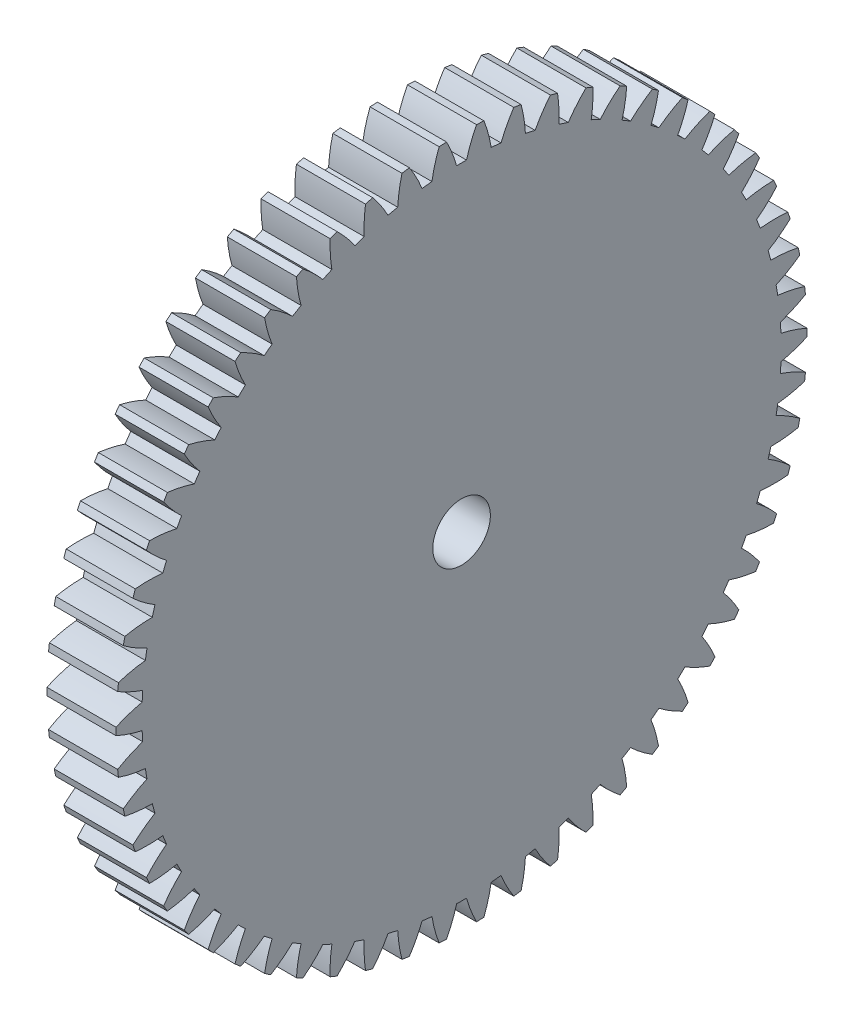
SolidWorks part; units mm, degrees
ref_plane "Plane1" through (0, 0, 0) normal (0, 0, 1) x (1, 0, 0)
ref_plane "Plane2" through (0, 0, 0) normal (0, 1, 0) x (1, 0, 0)
ref_plane "Plane3" through (0, 0, 0) normal (1, 0, 0) x (0, 0, -1)
other "Configuration Table"
sketch "HoldingSke" plane through (0, 0, 0) normal (0, 1, 0) x (1, 0, 0)
  line L0 (0, 0) -> (0.5299, -0.848)
  line L1 (-15, 0) -> (100, 0) construction
  line L2 (0, 0) -> (-2.1039, 2.3779)
  line L3 (0, 0) -> (-11.863, 4.5341)
  line L4 (0, 0) -> (4.5764, 7.3237)
  line L5 (0, 0) -> (-46.8476, -17.4728)
  line L6 (0, 0) -> (-4.9738, -3.3558)
  line L7 (-2.1039, 2.3779) -> (8.6586, 51.2059)
  line L8 (-76.2, 54.61) -> (-75.3, 54.61)
  line L9 (-71.009, 38.7566) -> (-53.1078, 45.2721)
  line L10 (-76.2, 71.12) -> (104.1128, 71.12)
  line L11 (0, 0) -> (-6, 0)
  line L12 (-76.2, 101.6) -> (-76.162, 101.6)
  line L13 (24.9733, 27.94) -> (52.9518, 28.4284)
  line L14 (24.9733, 27.94) -> (24.9743, 27.94)
  line L15 (24.9733, 27.94) -> (100.4006, 29.5858)
  line L16 (-63.627, -1) -> (-12.827, -1)
  circle A0 centre (0, 0) radius 2.5
  circle A1 centre (0, 0) radius 27.749
  circle A2 centre (0, 0) radius 37.5
  circle A3 centre (0, 0) radius 2.5
  dimension "MHD" = 55.498
  dimension "Hub_dia" = 75
  dimension "Bore" = 5
  dimension "MBD" = 5
  dimension "Num_teeth" = 58
  dimension "Pitch" = 1
  dimension "Overall_len" = 50
  dimension "Show_teeth" = 58
  dimension "Thickness" = 6
  dimension "OAL" = 50.0001
  dimension "T_dim" = 0.9
  dimension "Ap" = 20
  dimension "H" = 19.05
  dimension "Pitch_radius" = 180.3128
  dimension "Width" = 6
  dimension "Backlash" = 0.038
  dimension "Addendum_fac" = 1
  dimension "Dedendum_fac" = 1.25
  dimension "Clearance_fac" = 0.25
  dimension "Dedendum_add" = 0.001
  dimension "Module" = 1
sketch "BasProSke" plane through (0, 0, 0) normal (0, 1, 0) x (1, 0, 0)
  line L0 (-10, 0) -> (60, 0) construction
  line L1 (0, 0) -> (0, 30)
  line L2 (0, 0) -> (6, 0)
  line L3 (6, 0) -> (6, 30)
  line L4 (6, 30) -> (0, 30)
  dimension "Thickness" = 6
  dimension "Diameter" = 60
revolve "Base-Revolve" add sketch "BasProSke" angle 360 about L0
sketch "TooCutSke" plane through (0, 0, 0) normal (1, 0, 0) x (0, 0, -1)
  line L1 (0, 0) -> (0, 107) construction
  line L2 (0, 0) -> (-0.8518, 28.9875) construction
  line L3 (0, 0) -> (-3.1391, 57.8971) construction
  line L4 (-0.8518, 28.9875) -> (-1.5695, 28.9486) construction
  arc A0 (0.4315, 27.7456) -> (-0.4315, 27.7456) centre (0, 0) ccw
  arc A1 (1.3156, 29.9966) -> (-1.3156, 29.9966) centre (0, 0) ccw
  circle A2 centre (0, 0) radius 29 construction
  circle A3 centre (0, 0) radius 27.2511 construction
  arc A4 (-0.4315, 27.7456) -> (-1.3156, 29.9966) centre (-11.6117, 24.6534) ccw
  arc A5 (1.3156, 29.9966) -> (0.4315, 27.7456) centre (11.6117, 24.6534) ccw
  dimension "Root_dia" = 55.498
  dimension "Overcut_dia" = 60.0508
  dimension "Pitch_dia" = 58
  dimension "Base_dia" = 54.5022
  dimension "Flank_rad" = 11.6
  dimension "Half_ang" = 3.103
  dimension "Half_CT" = 0.7188
extrude "ToothCut" cut sketch "TooCutSke" along normal through all
fillet "Breaks" [suppressed] radius 0.02
fillet "RootFillets" [suppressed] radius 0.251
pattern_circular "TeethCuts" count 58 every 6.207 about axis through (-10, 0, 0) along (1, 0, 0) of "ToothCut", "RootFillets", "Breaks"
sketch "HubNeaOneSke" plane through (0, 0, 0) normal (-1, 0, 0) x (0, 0, 1)
  circle A0 centre (0, 0) radius 27.749
  dimension "Diameter" = 55.498
extrude "HubNearOne" [suppressed] add sketch "HubNeaOneSke" along normal blind 44.0001
sketch "HubNeaBotSke" plane through (0, 0, 0) normal (-1, 0, 0) x (0, 0, 1)
  circle A0 centre (0, 0) radius 27.749
  dimension "Diameter" = 55.498
extrude "HubNearBoth" [suppressed] add sketch "HubNeaBotSke" along normal blind 22
ref_plane "FarPln" through (6, 0, 0) normal (1, 0, 0) x (0, 0, -1)
sketch "HubFarSke" plane through (6, 0, 0) normal (1, 0, 0) x (0, 0, -1)
  circle A0 centre (0, 0) radius 27.749
  dimension "Diameter" = 55.498
extrude "HubFar" [suppressed] add sketch "HubFarSke" along normal blind 22
sketch "BorSke" plane through (0, 0, 0) normal (1, 0, 0) x (0, 0, -1)
  circle A0 centre (0, 0) radius 2.5
  dimension "Diameter" = 5
extrude "Bore" cut sketch "BorSke" along normal mid plane 100.0001
sketch "KeySke" plane through (0, 0, 0) normal (1, 0, 0) x (0, 0, -1)
  line L0 (-1, 0) -> (-1, 3.4)
  line L1 (-1, 3.4) -> (1, 3.4)
  line L2 (1, 3.4) -> (1, 0)
  line L3 (0, 0) -> (0, 34) construction
  line L4 (-1, 0) -> (1, 0)
  dimension "Offset" = 3.4
  dimension "Width" = 2
extrude "Keyway" [suppressed] cut sketch "KeySke" along normal mid plane 100.0001
pattern_circular "Keyway2" [suppressed] count 2 every 90 about axis through (-10, 0, 0) along (1, 0, 0)
equation "' \"Module@HoldingSke\" = 6.35"
equation "' \"Num_teeth@HoldingSke\" = 12"
equation "' \"Ap@HoldingSke\" =  20"
equation "' \"Ap@HoldingSke\" = 20"
equation "' \"Width@HoldingSke\" = 0.5 * 25.4"
equation "' \"Hub_dia@HoldingSke\"= 1 * 25.4"
equation "' \"Hub_dia@HoldingSke\" = 1 * 25.4"
equation "' \"Overall_len@HoldingSke\" = 1.0 * 25.4"
equation "' \"Bore@HoldingSke\" = 0.75 * 25.4"
equation "' \"T_dim@HoldingSke\" = 0.1 * 25.4"
equation "' \"Width@KeySke\" = 0.25 * 25.4"
equation "' \"Show_teeth@HoldingSke\" = 13"
equation "' \"Backlash@HoldingSke\" = 0.009 * 25.4"
equation "' \"Addendum_fac@HoldingSke\" = 1.0"
equation "' \"Dedendum_fac@HoldingSke\" = 1.25"
equation "' \"Dedendum_add@HoldingSke\" = 0.00005 * 25.4"
equation "' \"Clearance_fac@HoldingSke\" = 0.25"
equation "\"Pitch@HoldingSke\" = 1 / \"Module@HoldingSke\""
equation "\"Overcut_dia@TooCutSke\" = (\"Num_teeth@HoldingSke\" + 2 * \"Addendum_fac@HoldingSke\") / \"Pitch@HoldingSke\" + 0.002 * 25.4"
equation "\"Pitch_dia@TooCutSke\" = \"Num_teeth@HoldingSke\" / \"Pitch@HoldingSke\""
equation "\"Base_dia@TooCutSke\" = \"Num_teeth@HoldingSke\" / \"Pitch@HoldingSke\" * cos((\"Ap@HoldingSke\"  * 3.14159265 / 180))"
equation "\"Root_dia@TooCutSke\" = (\"Num_teeth@HoldingSke\" + 2) / \"Pitch@HoldingSke\" - 2 * (\"Addendum_fac@HoldingSke\" + \"Dedendum_fac@HoldingSke\") / \"Pitch@HoldingSke\" - \"Dedendum_add@HoldingSke\" * 2"
equation "\"Half_ang@TooCutSke\" = 180 / \"Num_teeth@HoldingSke\""
equation "\"Half_CT@TooCutSke\" = \"Num_teeth@HoldingSke\" / \"Pitch@HoldingSke\" * sin((3.14159265 / 2 / \"Num_teeth@HoldingSke\")) / 2 - 7 * \"Backlash@HoldingSke\" / 4"
equation "\"Flank_rad@TooCutSke\" = \"Num_teeth@HoldingSke\" / \"Pitch@HoldingSke\" / 5"
equation "\"Radius@RootFillets\" = \"Clearance_fac@HoldingSke\" / \"Pitch@HoldingSke\" + \"Dedendum_add@HoldingSke\""
equation "\"Break_rad@Breaks\" = 0.02 / \"Pitch@HoldingSke\""
equation "\"Thickness@HoldingSke\" = \"Width@HoldingSke\""
equation "\"OAL@HoldingSke\" = \"Thickness@HoldingSke\""
equation "\"MHD@HoldingSke\" = (\"Num_teeth@HoldingSke\" + 2) / \"Pitch@HoldingSke\" - 2 * (\"Addendum_fac@HoldingSke\" + \"Dedendum_fac@HoldingSke\")  / \"Pitch@HoldingSke\" - \"Dedendum_add@HoldingSke\" * 2"
equation "\"MBD@HoldingSke\" = (\"Num_teeth@HoldingSke\" + 2) / \"Pitch@HoldingSke\" - 2 * (\"Addendum_fac@HoldingSke\" + \"Dedendum_fac@HoldingSke\")  / \"Pitch@HoldingSke\" - \"Dedendum_add@HoldingSke\" * 2 - 0.002 * 25.4"
equation "\"MHD@HoldingSke\" = ((sgn( \"MHD@HoldingSke\" - \"Hub_dia@HoldingSke\" )-1)*( \"MHD@HoldingSke\" - \"Hub_dia@HoldingSke\" ))/-2+ \"Hub_dia@HoldingSke\""
equation "\"MBD@HoldingSke\" = ((sgn( \"MBD@HoldingSke\" - \"Bore@HoldingSke\" )-1)*( \"MBD@HoldingSke\" - \"Bore@HoldingSke\" ))/-2+ \"Bore@HoldingSke\""
equation "\"OAL@HoldingSke\" = ((sgn( \"OAL@HoldingSke\" - \"Overall_len@HoldingSke\" )+1)*( \"OAL@HoldingSke\" - \"Overall_len@HoldingSke\" ))/2 + \"Overall_len@HoldingSke\" + 0.000002 * 25.4"
equation "\"Num_teeth@TeethCuts\" = int( \"Show_teeth@HoldingSke\" ) + 1"
equation "\"Num_teeth@TeethCuts\" = ((sgn( \"Num_teeth@TeethCuts\" - \"Num_teeth@HoldingSke\" )-1)*( \"Num_teeth@TeethCuts\" - \"Num_teeth@HoldingSke\" ))/-2+ \"Num_teeth@HoldingSke\""
equation "\"Num_teeth@TeethCuts\" = ((sgn( \"Num_teeth@TeethCuts\" - 2.0)+1)*( \"Num_teeth@TeethCuts\" - 2.0))/2 +2.0"
equation "\"Angle@TeethCuts\" = 360.0 / \"Num_teeth@HoldingSke\""
equation "\"Diameter@BasProSke\" = (\"Num_teeth@HoldingSke\" + 2 * \"Addendum_fac@HoldingSke\") / \"Pitch@HoldingSke\""
equation "\"Thickness@BasProSke\"  = \"Thickness@HoldingSke\""
equation "' \"Fillet_rad@BasProSke\" =  \"Thickness@HoldingSke\" * 0.05"
equation "' \"Fillet_rad@BasProSke\" = \"Thickness@HoldingSke\" * 0.05"
equation "\"MHD@HoldingSke\" = ((sgn( \"MHD@HoldingSke\" - \"Root_dia@TooCutSke\" )-1)*( \"MHD@HoldingSke\" - \"Root_dia@TooCutSke\" ))/-2+ \"Root_dia@TooCutSke\""
equation "\"Diameter@HubNeaOneSke\" = \"MHD@HoldingSke\""
equation "\"Length@HubNearOne\" = \"OAL@HoldingSke\" - \"Thickness@BasProSke\""
equation "\"Diameter@HubNeaBotSke\" = \"MHD@HoldingSke\""
equation "\"Length@HubNearBoth\" = ( \"OAL@HoldingSke\" - \"Thickness@BasProSke\" ) / 2.0"
equation "\"Thickness@FarPln\" = \"Thickness@BasProSke\""
equation "\"Diameter@HubFarSke\" = \"MHD@HoldingSke\""
equation "\"Length@HubFar\" = ( \"OAL@HoldingSke\" - \"Thickness@BasProSke\" ) / 2.0"
equation "\"Diameter@BorSke\" = \"MBD@HoldingSke\""
equation "\"D1@Bore\" = \"OAL@HoldingSke\" * 2.0"
equation "\"D1@Keyway\" = \"OAL@HoldingSke\" * 2.0"
equation "\"Offset@KeySke\" = \"T_dim@HoldingSke\" + \"MBD@HoldingSke\" / 2.0"
